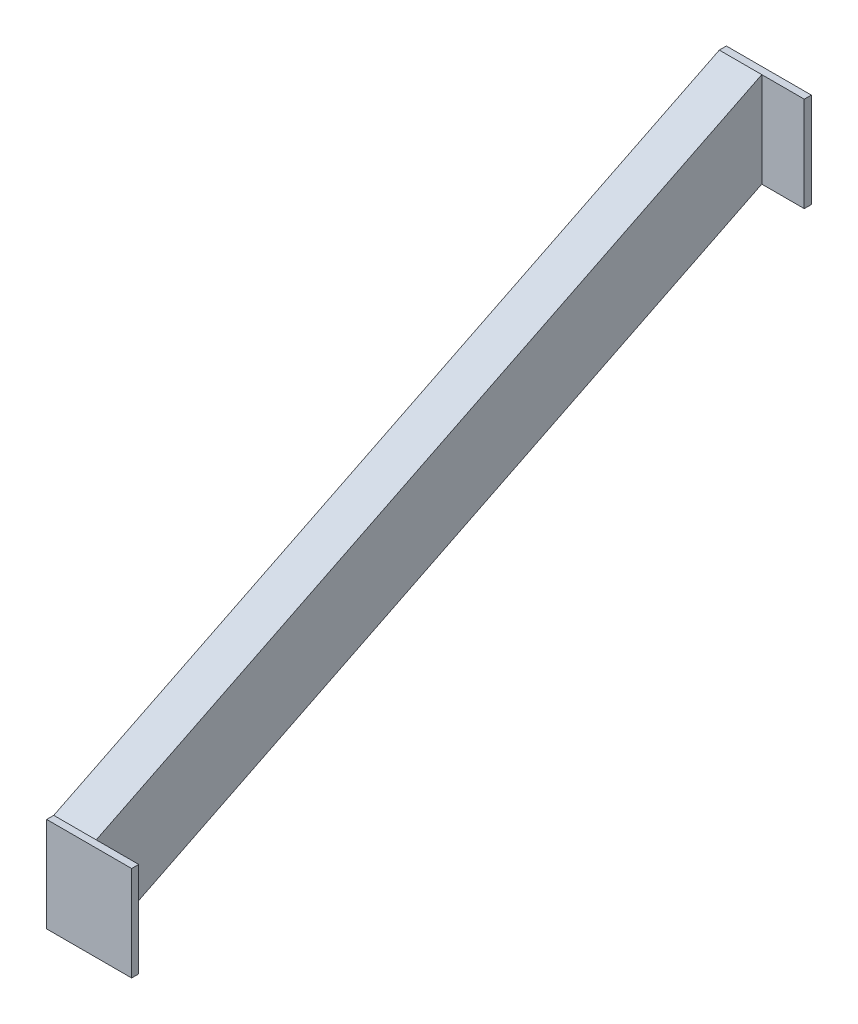
SolidWorks part; units mm, degrees
ref_plane "Front Plane" through (0, 0, 0) normal (0, 0, 1) x (1, 0, 0)
ref_plane "Top Plane" through (0, 0, 0) normal (0, 1, 0) x (1, 0, 0)
ref_plane "Right Plane" through (0, 0, 0) normal (1, 0, 0) x (0, 0, -1)
sketch "Sketch2" plane through (0, 0, 0) normal (1, 0, 0) x (0, 0, -1)
  line L0 (0, 0) -> (0, 170.1037)
  line L1 (0, 0) -> (1193.8, 0) construction
  line L2 (1193.8, 0) -> (1193.8, 762) construction
  line L3 (0, 170.1037) -> (1193.8, 762)
  line L4 (1193.8, 762) -> (1193.8, 591.8963)
  line L5 (1193.8, 591.8963) -> (0, 0)
  dimension "D1" = 152.4
  dimension "D2" = 1193.8
  dimension "D3" = 762
extrude "Boss-Extrude1" add sketch "Sketch2" along normal blind 76.2
sketch "Sketch5" plane through (0, 0, -1193.8) normal (0, 0, -1) x (-1, 0, 0)
  line L0 (-76.2, 591.8963) -> (0, 591.8963) construction
  line L1 (0, 762) -> (-152.4, 762)
  line L2 (0, 762) -> (0, 591.8963)
  line L3 (0, 591.8963) -> (-152.4, 591.8963)
  line L4 (-152.4, 762) -> (-152.4, 591.8963)
  dimension "D2" = 152.4
extrude "Boss-Extrude3" add sketch "Sketch5" along normal blind 12.7
sketch "Sketch6" plane through (0, 0, 0) normal (0, 0, 1) x (1, 0, 0)
  line L0 (76.2, 170.1037) -> (0, 170.1037) construction
  line L1 (0, 0) -> (152.4, 0)
  line L2 (0, 0) -> (0, 170.1037)
  line L3 (0, 170.1037) -> (152.4, 170.1037)
  line L4 (152.4, 0) -> (152.4, 170.1037)
  dimension "D1" = 152.4
extrude "Boss-Extrude4" add sketch "Sketch6" along normal blind 12.7
